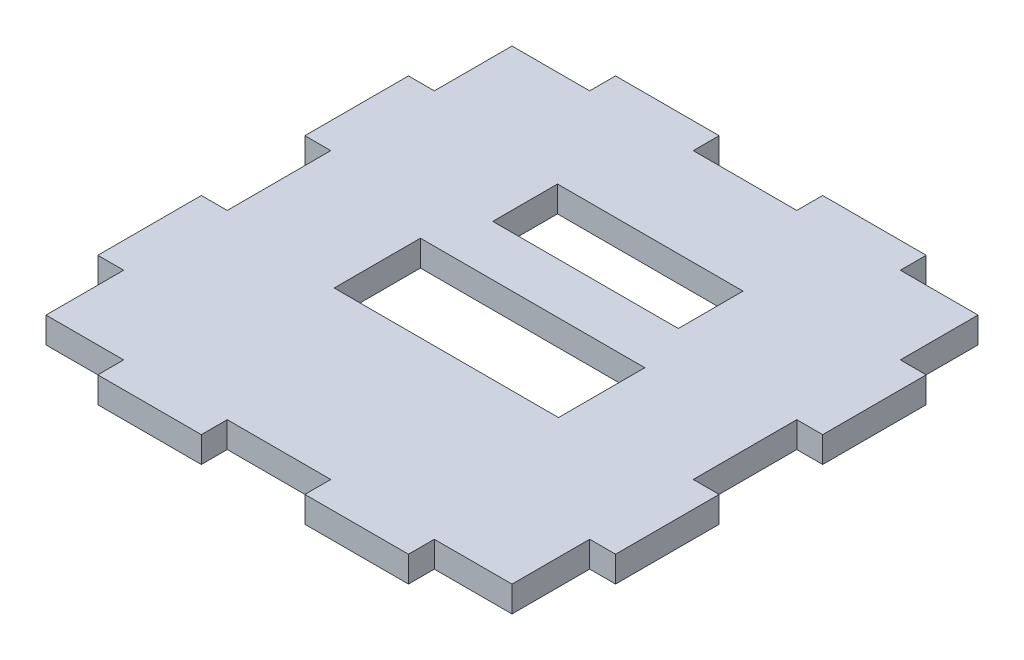
SolidWorks part; units mm, degrees
ref_plane "Front Plane" through (0, 0, 0) normal (0, 0, 1) x (1, 0, 0)
ref_plane "Top Plane" through (0, 0, 0) normal (0, 1, 0) x (1, 0, 0)
ref_plane "Right Plane" through (0, 0, 0) normal (1, 0, 0) x (0, 0, -1)
sketch "Sketch1" plane through (0, 0, 0) normal (0, 1, 0) x (1, 0, 0)
  line L1 (-186.2722, 187.3213) -> (4.2278, 187.3213)
  line L2 (-186.2722, 187.3213) -> (-186.2722, -3.1787)
  line L3 (-186.2722, -3.1787) -> (4.2278, -3.1787)
  line L4 (4.2278, 187.3213) -> (4.2278, -3.1787)
  dimension "D1" = 190.5
  dimension "D2" = 190.5
extrude "Boss-Extrude1" add sketch "Sketch1" along normal blind 9.525
sketch "Sketch2" plane through (0, 9.525, 0) normal (0, 1, 0) x (1, 0, 0)
  line L0 (-186.2722, -3.1787) -> (4.2278, -3.1787) construction
  line L1 (-5.2972, -3.1787) -> (4.2278, -3.1787)
  line L2 (-5.2972, -3.1787) -> (-5.2972, 34.9213)
  line L3 (-5.2972, 34.9213) -> (4.2278, 34.9213)
  line L4 (4.2278, -3.1787) -> (4.2278, 34.9213)
  line L5 (4.2278, -3.1787) -> (4.2278, 187.3213) construction
  dimension "D1" = 38.1
  dimension "D2" = 9.525
extrude "Cut-Extrude1" cut sketch "Sketch2" against normal blind 9.525
sketch "Sketch3" plane through (0, 9.525, 0) normal (0, 1, 0) x (1, 0, 0)
  line L0 (4.2278, 34.9213) -> (4.2278, 187.3213) construction
  line L1 (4.2278, 73.0213) -> (-5.2972, 73.0213)
  line L2 (4.2278, 73.0213) -> (4.2278, 111.1213)
  line L3 (4.2278, 111.1213) -> (-5.2972, 111.1213)
  line L4 (-5.2972, 73.0213) -> (-5.2972, 111.1213)
  dimension "D1" = 9.525
  dimension "D2" = 38.1
  dimension "D3" = 38.1
extrude "Cut-Extrude2" cut sketch "Sketch3" against normal blind 9.525
sketch "Sketch4" plane through (0, 9.525, 0) normal (0, 1, 0) x (1, 0, 0)
  line L0 (4.2278, 111.1213) -> (4.2278, 187.3213) construction
  line L1 (4.2278, 149.2213) -> (-5.2972, 149.2213)
  line L2 (4.2278, 149.2213) -> (4.2278, 187.3213)
  line L3 (4.2278, 187.3213) -> (-5.2972, 187.3213)
  line L4 (-5.2972, 149.2213) -> (-5.2972, 187.3213)
  line L5 (4.2278, 187.3213) -> (-186.2722, 187.3213) construction
  dimension "D1" = 9.525
  dimension "D2" = 38.1
extrude "Cut-Extrude3" cut sketch "Sketch4" against normal blind 9.525
sketch "Sketch5" plane through (0, 0, 0) normal (0, -1, 0) x (1, 0, 0)
  line L0 (-186.2722, 3.1787) -> (-5.2972, 3.1787) construction
  line L1 (-176.7472, 3.1787) -> (-186.2722, 3.1787)
  line L2 (-176.7472, 3.1787) -> (-176.7472, -34.9213)
  line L3 (-176.7472, -34.9213) -> (-186.2722, -34.9213)
  line L4 (-186.2722, 3.1787) -> (-186.2722, -34.9213)
  line L5 (-186.2722, -187.3213) -> (-186.2722, 3.1787) construction
  dimension "D1" = 9.525
  dimension "D2" = 38.1
extrude "Cut-Extrude4" cut sketch "Sketch5" against normal blind 9.525
sketch "Sketch6" plane through (0, 0, 0) normal (0, -1, 0) x (1, 0, 0)
  line L0 (-186.2722, -187.3213) -> (-186.2722, -34.9213) construction
  line L1 (-186.2722, -73.0213) -> (-176.7472, -73.0213)
  line L2 (-186.2722, -73.0213) -> (-186.2722, -111.1213)
  line L3 (-186.2722, -111.1213) -> (-176.7472, -111.1213)
  line L4 (-176.7472, -73.0213) -> (-176.7472, -111.1213)
  dimension "D1" = 38.1
  dimension "D2" = 9.525
  dimension "D3" = 38.1
extrude "Cut-Extrude5" cut sketch "Sketch6" against normal blind 9.525
sketch "Sketch7" plane through (0, 0, 0) normal (0, -1, 0) x (1, 0, 0)
  line L0 (-186.2722, -187.3213) -> (-186.2722, -111.1213) construction
  line L1 (-186.2722, -149.2213) -> (-176.7472, -149.2213)
  line L2 (-186.2722, -149.2213) -> (-186.2722, -187.3213)
  line L3 (-186.2722, -187.3213) -> (-176.7472, -187.3213)
  line L4 (-176.7472, -149.2213) -> (-176.7472, -187.3213)
  line L5 (-5.2972, -187.3213) -> (-186.2722, -187.3213) construction
  dimension "D1" = 9.525
extrude "Cut-Extrude6" cut sketch "Sketch7" against normal blind 9.525
sketch "Sketch8" plane through (0, 0, 0) normal (0, -1, 0) x (1, 0, 0)
  line L0 (-5.2972, -187.3213) -> (-5.2972, -149.2213) construction
  line L1 (-5.2972, -177.7963) -> (-33.8722, -177.7963)
  line L2 (-5.2972, -177.7963) -> (-5.2972, -187.3213)
  line L3 (-5.2972, -187.3213) -> (-33.8722, -187.3213)
  line L4 (-33.8722, -177.7963) -> (-33.8722, -187.3213)
  line L5 (-5.2972, -187.3213) -> (-176.7472, -187.3213) construction
  dimension "D1" = 28.575
  dimension "D2" = 9.525
extrude "Cut-Extrude7" cut sketch "Sketch8" against normal blind 9.525
sketch "Sketch9" plane through (0, 0, 0) normal (0, -1, 0) x (1, 0, 0)
  line L0 (-33.8722, -187.3213) -> (-176.7472, -187.3213) construction
  line L1 (-71.9722, -187.3213) -> (-110.0722, -187.3213)
  line L2 (-71.9722, -187.3213) -> (-71.9722, -177.7963)
  line L3 (-71.9722, -177.7963) -> (-110.0722, -177.7963)
  line L4 (-110.0722, -187.3213) -> (-110.0722, -177.7963)
  dimension "D1" = 38.1
  dimension "D2" = 38.1
  dimension "D3" = 9.525
extrude "Cut-Extrude8" cut sketch "Sketch9" against normal blind 9.525
sketch "Sketch10" plane through (0, 0, 0) normal (0, -1, 0) x (1, 0, 0)
  line L0 (-110.0722, -187.3213) -> (-176.7472, -187.3213) construction
  line L1 (-148.1722, -187.3213) -> (-176.7472, -187.3213)
  line L2 (-148.1722, -187.3213) -> (-148.1722, -177.7963)
  line L3 (-148.1722, -177.7963) -> (-176.7472, -177.7963)
  line L4 (-176.7472, -187.3213) -> (-176.7472, -177.7963)
  line L5 (-176.7472, -187.3213) -> (-176.7472, -149.2213) construction
  dimension "D1" = 38.1
  dimension "D2" = 9.525
extrude "Cut-Extrude9" cut sketch "Sketch10" against normal blind 9.525
sketch "Sketch11" plane through (0, 0, 0) normal (0, -1, 0) x (-1, 0, 0)
  line L0 (176.7472, 34.9213) -> (176.7472, -3.1787) construction
  line L1 (176.7472, 6.3463) -> (148.1722, 6.3463)
  line L2 (176.7472, 6.3463) -> (176.7472, -3.1787)
  line L3 (176.7472, -3.1787) -> (148.1722, -3.1787)
  line L4 (148.1722, 6.3463) -> (148.1722, -3.1787)
  line L5 (176.7472, -3.1787) -> (5.2972, -3.1787) construction
  dimension "D1" = 28.575
  dimension "D2" = 9.525
extrude "Cut-Extrude11" cut sketch "Sketch11" against normal blind 9.525
sketch "Sketch12" plane through (0, 0, 0) normal (0, -1, 0) x (1, 0, 0)
  line L0 (-148.1722, 3.1787) -> (-5.2972, 3.1787) construction
  line L1 (-110.0722, 3.1787) -> (-71.9722, 3.1787)
  line L2 (-110.0722, 3.1787) -> (-110.0722, -6.3463)
  line L3 (-110.0722, -6.3463) -> (-71.9722, -6.3463)
  line L4 (-71.9722, 3.1787) -> (-71.9722, -6.3463)
  line L5 (-148.1722, -6.3463) -> (-148.1722, 3.1787) construction
  dimension "D1" = 38.1
  dimension "D2" = 9.525
  dimension "D3" = 38.1
extrude "Cut-Extrude12" cut sketch "Sketch12" against normal blind 9.525
sketch "Sketch14" plane through (0, 0, 0) normal (0, -1, 0) x (-1, 0, 0)
  line L0 (71.9722, -3.1787) -> (5.2972, -3.1787) construction
  line L1 (33.8722, -3.1787) -> (5.2972, -3.1787)
  line L2 (33.8722, -3.1787) -> (33.8722, 6.3463)
  line L3 (33.8722, 6.3463) -> (5.2972, 6.3463)
  line L4 (5.2972, -3.1787) -> (5.2972, 6.3463)
  line L5 (5.2972, 34.9213) -> (5.2972, -3.1787) construction
  line L6 (71.9722, 6.3463) -> (71.9722, -3.1787) construction
  dimension "D1" = 38.1
  dimension "D2" = 9.525
extrude "Cut-Extrude13" cut sketch "Sketch14" against normal blind 9.525
sketch "Sketch15" plane through (0, 0, 0) normal (0, -1, 0) x (1, 0, 0)
  line L1 (-124.4082, -118.381) -> (-56.1457, -118.381)
  line L2 (-124.4082, -118.381) -> (-124.4082, -142.1935)
  line L3 (-124.4082, -142.1935) -> (-56.1457, -142.1935)
  line L4 (-56.1457, -118.381) -> (-56.1457, -142.1935)
  line L5 (-132.4307, -63.1955) -> (-49.8807, -63.1955)
  line L6 (-132.4307, -63.1955) -> (-132.4307, -94.9455)
  line L7 (-132.4307, -94.9455) -> (-49.8807, -94.9455)
  line L8 (-49.8807, -63.1955) -> (-49.8807, -94.9455)
  dimension "D1" = 68.2625
  dimension "D2" = 23.8125
  dimension "D3" = 82.55
  dimension "D4" = 31.75
extrude "Cut-Extrude14" cut sketch "Sketch15" against normal blind 9.525 contours L2 L3 L4 L1
sketch "Sketch16" plane through (0, 0, 0) normal (0, -1, 0) x (1, 0, 0)
  line L1 (-132.3584, -67.972) -> (-49.8084, -67.972)
  line L2 (-132.3584, -67.972) -> (-132.3584, -99.722)
  line L3 (-132.3584, -99.722) -> (-49.8084, -99.722)
  line L4 (-49.8084, -67.972) -> (-49.8084, -99.722)
  dimension "D1" = 82.55
  dimension "D2" = 31.75
extrude "Cut-Extrude15" cut sketch "Sketch16" against normal blind 9.525
